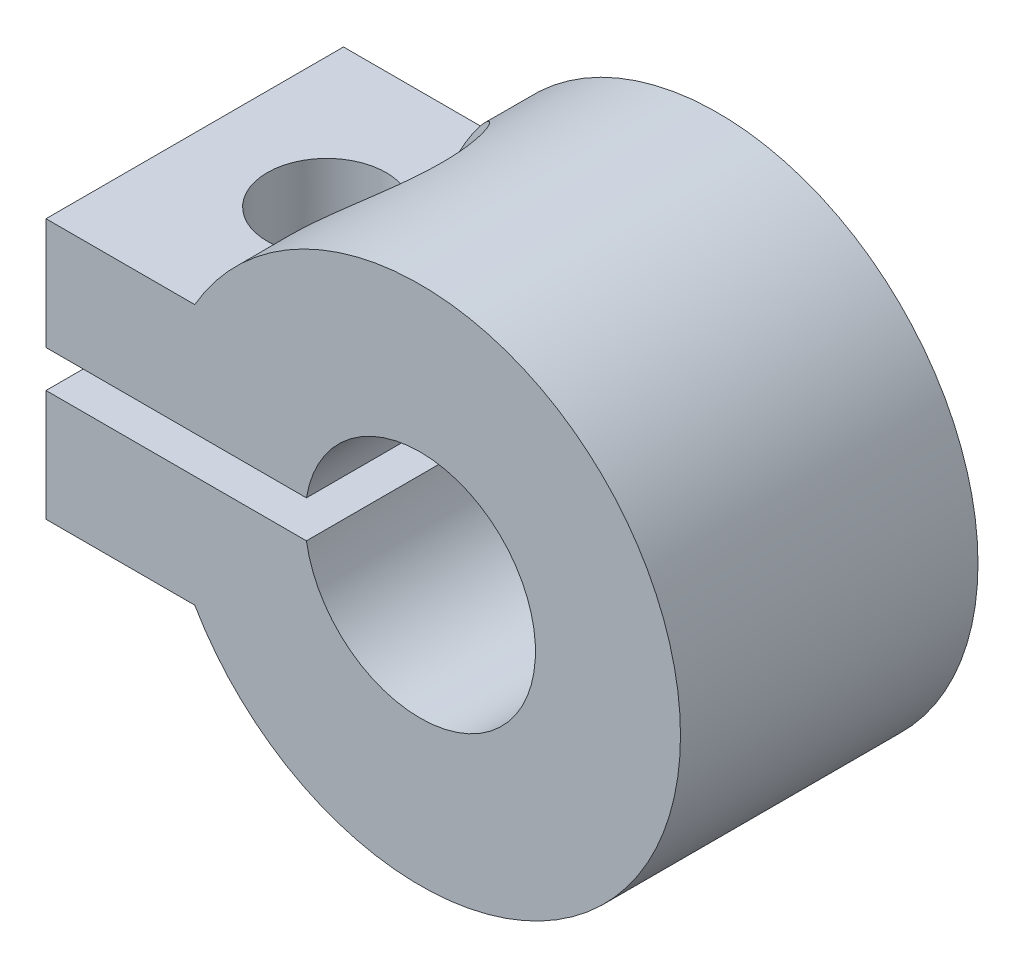
SolidWorks part; units mm, degrees
ref_plane "Front Plane" through (0, 0, 0) normal (0, 0, 1) x (1, 0, 0)
ref_plane "Top Plane" through (0, 0, 0) normal (0, 1, 0) x (1, 0, 0)
ref_plane "Right Plane" through (0, 0, 0) normal (1, 0, 0) x (0, 0, -1)
sketch "Sketch1" plane through (0, 0, 0) normal (0, 0, 1) x (1, 0, 0)
  line L0 (-6.0622, 3.5) -> (-10.0622, 3.5)
  line L1 (-10.0622, 3.5) -> (-10.0622, 0.5)
  line L2 (-10.0622, 0.5) -> (-3.0594, 0.5)
  line L3 (-3.0594, -0.5) -> (-10.0622, -0.5)
  line L4 (-10.0622, -0.5) -> (-10.0622, -3.5)
  line L5 (-10.0622, -3.5) -> (-6.0622, -3.5)
  line L6 (-10.0622, -0.5) -> (-10.0622, 0.5) construction
  arc A0 (-3.0594, -0.5) -> (-3.0594, 0.5) centre (0, 0) ccw
  arc A1 (-6.0622, -3.5) -> (-6.0622, 3.5) centre (0, 0) ccw
  point P11 (0, 0)
  point P13 (-10.0622, 0)
  dimension "D2" = 7
  dimension "D3" = 3.1
  dimension "D1" = 3
  dimension "D4" = 0.5
  dimension "D5" = 4
extrude "Boss-Extrude1" add sketch "Sketch1" along normal blind 8
sketch "Sketch2" plane through (0, 3.5, 0) normal (0, 1, 0) x (1, 0, 0)
  line L0 (-10.0622, -8) -> (-10.0622, 0) construction
  circle A0 centre (-6.5622, -3.9514) radius 1.6
  circle A1 centre (-6.5622, -3.9514) radius 3.1 construction
  point P2 (-10.0622, -4)
  dimension "D1" = 6.2
  dimension "D2" = 3.2
  dimension "D3" = 3.5
extrude "Cut-Extrude1" cut sketch "Sketch2" against normal through all
sketch "Sketch3" plane through (0, 3.5, 0) normal (0, 1, 0) x (1, 0, 0)
  circle A0 centre (-6.5622, -3.9514) radius 3.1
  dimension "D1" = 6.2
extrude "Cut-Extrude2" cut sketch "Sketch3" along normal through all
sketch "Sketch4" plane through (0, -3.5, 0) normal (0, -1, 0) x (1, 0, 0)
  circle A0 centre (-6.5622, 3.9514) radius 3.1
  dimension "D1" = 6.2
extrude "Cut-Extrude3" cut sketch "Sketch4" along normal through all contours A0
